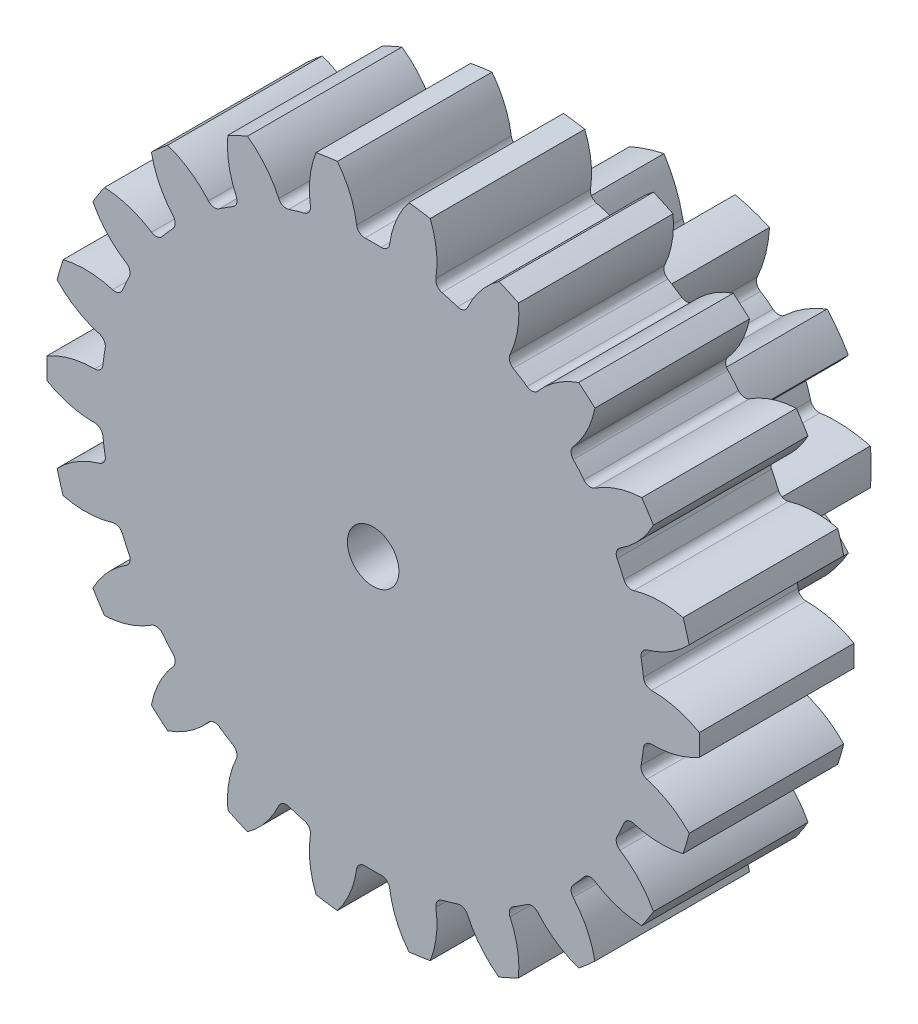
SolidWorks part; units mm, degrees
ref_plane "Front" through (0, 0, 0) normal (0, 0, 1) x (1, 0, 0)
ref_plane "Top" through (0, 0, 0) normal (0, 1, 0) x (1, 0, 0)
ref_plane "Right" through (0, 0, 0) normal (1, 0, 0) x (0, 0, -1)
sketch "Sketch1" plane through (0, 0, 0) normal (0, 0, 1) x (1, 0, 0)
  circle A0 centre (0, 0) radius 6.6667
  circle A1 centre (0, 0) radius 10
  circle A2 centre (0, 0) radius 8.3333
  dimension "D1" = 20
  dimension "D2" = 13.3333
  dimension "D3" = 16.6667
extrude "Boss-Extrude1" add sketch "Sketch1" along normal mid plane 10 contours A1
sketch "Sketch3" plane through (0, 0, 0) normal (0, 0, 1) x (1, 0, 0)
  line L0 (0, 0) -> (0, 10) construction
  line L1 (-1.3036, 8.2307) -> (1.3036, 8.2307) construction
  line L2 (-2.2285, 10.7719) -> (0, 4.6491) construction
  line L3 (0, 0) -> (3.0902, 9.5106) construction
  line L4 (1.3036, 8.2307) -> (3.7833, 7.4251) construction
  line L5 (0, 0) -> (-0.9018, 6.6054) construction
  circle A0 centre (0, 0) radius 10 construction
  arc A1 (-2.7219, 10.6579) -> (-0.9018, 6.6054) centre (-8.6908, 5.542) cw
  arc A2 (2.7219, 10.6579) -> (0.9018, 6.6054) centre (8.6908, 5.542) ccw
  arc A3 (0.9018, 6.6054) -> (-0.9018, 6.6054) centre (0, 0) ccw
  circle A4 centre (0, 0) radius 6.6667 construction
  circle A6 centre (0, 0) radius 8.3333 construction
  circle A7 centre (0, 0) radius 11
  arc A8 (2.7219, 10.6579) -> (-2.7219, 10.6579) centre (0, 0) ccw
  circle A9 centre (0, 0) radius 10 construction
  dimension "D3" = 18
  dimension "D2" = 20
extrude "Cut-Extrude1" cut sketch "Sketch3" against normal through all both and the other way through all
fillet "Fillet2" radius 0.5 2 edges at (0.9018, 6.6054, 0) (-0.9018, 6.6054, 0)
pattern_circular "CirPattern1" count 10 over 360 about axis through (0, 0, 0) along (0, 0, 1) of "Cut-Extrude1", "Fillet2"
sketch "Sketch4" plane through (0, 0, 5) normal (0, 0, 1) x (1, 0, 0)
  circle A0 centre (0, 0) radius 17.4167
  circle A1 centre (0, 0) radius 19
  circle A2 centre (0, 0) radius 15.8333
  dimension "D1" = 34.8333
  dimension "D2" = 38
  dimension "D3" = 31.6667
extrude "Boss-Extrude2" add sketch "Sketch4" along normal blind 9 separate body
sketch "Sketch5" plane through (0, 0, 14) normal (0, 0, 1) x (1, 0, 0)
  line L0 (0, 0) -> (0, 19) construction
  line L1 (-1.2425, 17.3723) -> (1.2425, 17.3723) construction
  line L2 (-0.9193, 15.8066) -> (0, 0) construction
  line L3 (-2.1565, 19.8834) -> (0, 13.9586) construction
  line L4 (0, 0) -> (2.704, 18.8066) construction
  line L5 (1.2425, 17.3723) -> (3.7022, 17.0186) construction
  circle A0 centre (0, 0) radius 19 construction
  arc A1 (-2.9634, 19.7792) -> (-0.9193, 15.8066) centre (-6.4237, 15.4865) cw
  arc A2 (2.9634, 19.7792) -> (0.9193, 15.8066) centre (6.4237, 15.4865) ccw
  circle A3 centre (0, 0) radius 15.8333 construction
  arc A4 (0.9193, 15.8066) -> (-0.9193, 15.8066) centre (0, 0) ccw
  circle A6 centre (0, 0) radius 17.4167 construction
  circle A7 centre (0, 0) radius 20
  arc A8 (2.9634, 19.7792) -> (-2.9634, 19.7792) centre (0, 0) ccw
  circle A9 centre (0, 0) radius 19 construction
  dimension "D2" = 20
  dimension "D3" = 8.182
extrude "Cut-Extrude2" cut sketch "Sketch5" against normal up to surface (9 mm away) up to face at (19, 0, 5)
fillet "Fillet3" radius 0.475 2 edges at (0.9193, 15.8066, 9.5) (-0.9193, 15.8066, 9.5)
pattern_circular "CirPattern2" count 22 over 360 about axis through (0, 0, 0) along (0, 0, 1) of "Cut-Extrude2", "Fillet3"
sketch "Sketch6" plane through (0, 0, 14) normal (0, 0, 1) x (1, 0, 0)
  circle A0 centre (0, 0) radius 1.5
  dimension "D1" = 3
extrude "Cut-Extrude3" cut sketch "Sketch6" against normal through all
equation "\"bot_n\"= 10'bottom number of teeth"
equation "\"bot_m\"= \"bot_od\" / ( \"bot_n\" + 2 )'bottom module"
equation "\"bot_p\"= \"bot_m\" * pi'bottom pitch"
equation "\"bot_d\"= \"bot_m\" * \"bot_n\"'bottom primitive diameter"
equation "\"bot_da\"= \"bot_d\" + 2 * \"bot_m\"'bottom head diamater"
equation "\"bot_df\"= \"bot_d\" - 2 * \"bot_m\"'bottom foot diameter"
equation "\"bot_od\"= 20'bottom outer diameter"
equation "\"D1@Sketch1\"=\"bot_od\""
equation "\"D2@Sketch1\"=\"bot_df\""
equation "\"D3@Sketch1\"=\"bot_d\""
equation "\"D3@Sketch3\"= 180 / \"bot_n\""
equation "\"D1@Fillet2\"=.3*\"bot_m\""
equation "\"top_n\"= 22'top number of teeth"
equation "\"top_od\"= 38'top outer diameter"
equation "\"top_m\"= \"top_od\" / ( \"top_n\" + 2 )'top module"
equation "\"top_p\"= \"top_m\" * pi'top pitch"
equation "\"top_d\"= \"top_m\" * \"top_n\"'top primitive diameter"
equation "\"top_da\"= \"top_d\" + 2 * \"top_m\"'top head diameter"
equation "\"top_df\"= \"top_d\" - 2 * \"top_m\"'top foot diamter"
equation "\"D1@CirPattern1\"= \"bot_n\""
equation "\"D1@Sketch4\"= \"top_m\" * \"top_n\""
equation "\"D2@Sketch4\"= (\"top_n\" + 2) * \"top_m\""
equation "\"D3@Sketch4\"=\"top_df\""
equation "\"D3@Sketch5\"= 180 / \"top_n\""
equation "\"D1@Fillet3\"=.3 * \"top_m\""
equation "\"D1@CirPattern2\"= \"top_n\""
